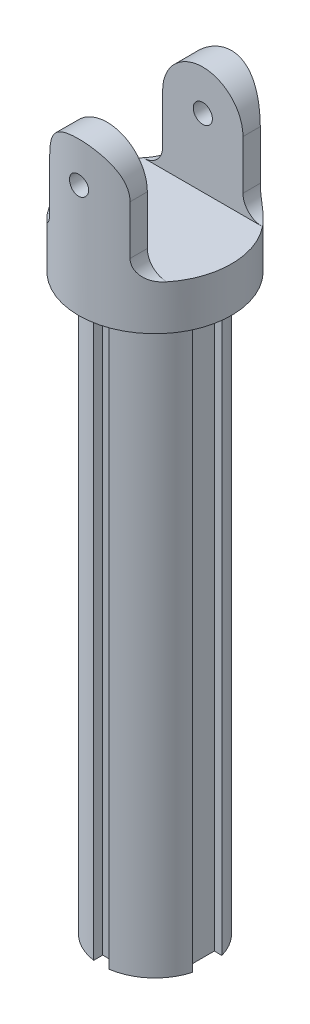
SolidWorks part; units mm, degrees
ref_plane "Front Plane" through (0, 0, 0) normal (0, 0, 1) x (1, 0, 0)
ref_plane "Top Plane" through (0, 0, 0) normal (0, 1, 0) x (1, 0, 0)
ref_plane "Right Plane" through (0, 0, 0) normal (1, 0, 0) x (0, 0, -1)
sketch "Sketch1" plane through (0, 0, 0) normal (0, 1, 0) x (1, 0, 0)
  circle A0 centre (0, 0) radius 6
  dimension "D1" = 12
extrude "Boss-Extrude1" add sketch "Sketch1" along normal blind 12
sketch "Sketch2" plane through (0, 0, 0) normal (1, 0, 0) x (0, 0, -1)
  line L0 (6, 12) -> (-6, 12) construction
  line L1 (-3.75, 12) -> (3.75, 12)
  line L2 (-3.75, 12) -> (-3.75, 3.5)
  line L3 (-3.75, 3.5) -> (3.75, 3.5)
  line L4 (3.75, 12) -> (3.75, 3.5)
  line L5 (-6, 0) -> (6, 0) construction
  point P8 (0, 3.5)
  dimension "D1" = 3.5
  dimension "D2" = 7.5
extrude "Cut-Extrude1" cut sketch "Sketch2" against normal through all both and the other way through all contours L2 L1 L4 L3
sketch "Sketch3" plane through (0, 0, 0) normal (0, 0, 1) x (1, 0, 0)
  line L0 (4.6837, 12) -> (-4.6837, 12) construction
  line L1 (-3.15, 8.85) -> (-3.15, 5)
  line L2 (-4.65, 3.5) -> (-4.6837, 3.5)
  line L3 (-4.6837, 12) -> (-4.6837, 3.5) construction
  line L4 (4.6837, 12) -> (-4.6837, 12)
  line L5 (-4.6837, 12) -> (-4.6837, 3.5)
  line L7 (0, -6.6) -> (0, 6.6) construction
  line L8 (4.6837, 12) -> (4.6837, 3.5)
  line L9 (4.65, 3.5) -> (4.6837, 3.5)
  line L10 (3.15, 8.85) -> (3.15, 5)
  arc A0 (3.15, 8.85) -> (-3.15, 8.85) centre (0, 8.85) ccw
  arc A1 (-3.15, 5) -> (-4.65, 3.5) centre (-4.65, 5) cw
  arc A2 (3.15, 5) -> (4.65, 3.5) centre (4.65, 5) ccw
  circle A3 centre (0, 8.85) radius 0.75
  dimension "D1" = 6.3
  dimension "D2" = 1.5
  dimension "D3" = 1.5
extrude "Cut-Extrude2" cut sketch "Sketch3" against normal through all both and the other way through all contours A1 L1 A0 L4 L5 L2 | L10 A2 L9 L8 L4 A0 | A3
sketch "Sketch4" plane through (0, 0, 0) normal (0, -1, 0) x (1, 0, 0)
  line L1 (-0.6, 5) -> (0.6, 5)
  line L2 (-0.6, 5) -> (-0.6, 3.5)
  line L3 (-0.6, 3.5) -> (0.6, 3.5)
  line L4 (0.6, 5) -> (0.6, 3.5)
  line L5 (-0.6, 5) -> (0.6, 3.5) construction
  line L6 (-0.6, 3.5) -> (0.6, 5) construction
  line L7 (5, 1.15) -> (3.5, 1.15)
  line L8 (5, 1.15) -> (5, -1.15)
  line L9 (5, -1.15) -> (3.5, -1.15)
  line L10 (3.5, 1.15) -> (3.5, -1.15)
  line L11 (5, 1.15) -> (3.5, -1.15) construction
  line L12 (5, -1.15) -> (3.5, 1.15) construction
  line L13 (-5, -1.15) -> (-3.5, -1.15)
  line L14 (-5, -1.15) -> (-5, 1.15)
  line L15 (-5, 1.15) -> (-3.5, 1.15)
  line L16 (-3.5, -1.15) -> (-3.5, 1.15)
  line L17 (-5, -1.15) -> (-3.5, 1.15) construction
  line L18 (-5, 1.15) -> (-3.5, -1.15) construction
  line L19 (-0.6, -5) -> (0.6, -5)
  line L20 (-0.6, -5) -> (-0.6, -3.5)
  line L21 (-0.6, -3.5) -> (0.6, -3.5)
  line L22 (0.6, -5) -> (0.6, -3.5)
  line L23 (-0.6, -5) -> (0.6, -3.5) construction
  line L24 (-0.6, -3.5) -> (0.6, -5) construction
  circle A0 centre (0, 0) radius 4.25
  point P3 (0, 4.25)
  point P8 (4.25, 0)
  point P13 (-4.25, 0)
  point P18 (0, -4.25)
  dimension "D4" = 8.5
  dimension "D1" = 2.3
  dimension "D2" = 1.2
  dimension "D3" = 1.5
extrude "Boss-Extrude2" add sketch "Sketch4" along normal blind 45 contours L22 A0 L9 L10 L7 L4 L3 L2 L15 L16 L13 L20 L21
